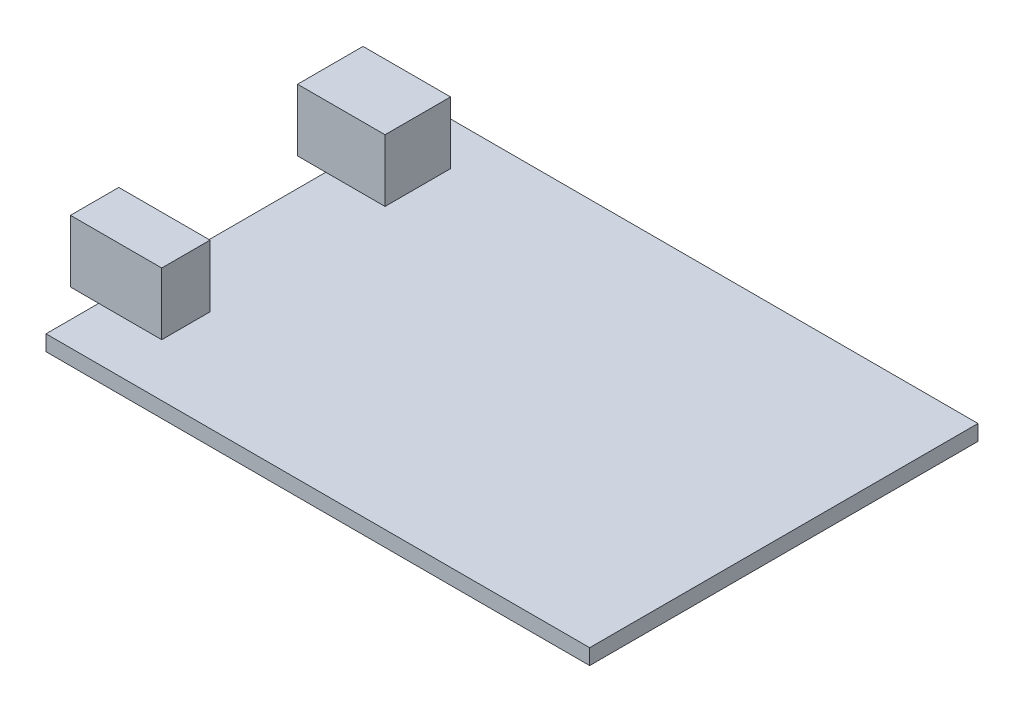
SolidWorks part; units mm, degrees
ref_plane "前视基准面" through (0, 0, 0) normal (0, 0, 1) x (1, 0, 0)
ref_plane "上视基准面" through (0, 0, 0) normal (0, 1, 0) x (1, 0, 0)
ref_plane "右视基准面" through (0, 0, 0) normal (1, 0, 0) x (0, 0, -1)
sketch "草图1" plane through (0, 0, 0) normal (0, 1, 0) x (1, 0, 0)
  line L1 (-22.2992, 9.5983) -> (47.7008, 9.5983)
  line L2 (-22.2992, 9.5983) -> (-22.2992, -40.4017)
  line L3 (-22.2992, -40.4017) -> (47.7008, -40.4017)
  line L4 (47.7008, 9.5983) -> (47.7008, -40.4017)
  line L5 (-22.2992, 9.5983) -> (47.7008, -40.4017) construction
  line L6 (-22.2992, -40.4017) -> (47.7008, 9.5983) construction
  point P4 (12.7008, -15.4017)
  dimension "D1" = 70
  dimension "D2" = 50
extrude "凸台-拉伸1" add sketch "草图1" along normal blind 2
sketch "草图2" plane through (0, 2, 0) normal (0, 1, 0) x (1, 0, 0)
  line L1 (-25.936, 4.055) -> (-14.6698, 4.055)
  line L2 (-25.936, 4.055) -> (-25.936, -4.3774)
  line L3 (-25.936, -4.3774) -> (-14.6698, -4.3774)
  line L4 (-14.6698, 4.055) -> (-14.6698, -4.3774)
  line L5 (-25.936, 4.055) -> (-14.6698, -4.3774) construction
  line L6 (-25.936, -4.3774) -> (-14.6698, 4.055) construction
  line L7 (-25.936, -27.3936) -> (-14.186, -27.3936)
  line L8 (-25.936, -27.3936) -> (-25.936, -33.6142)
  line L9 (-25.936, -33.6142) -> (-14.186, -33.6142)
  line L10 (-14.186, -27.3936) -> (-14.186, -33.6142)
  line L11 (-25.936, -27.3936) -> (-14.186, -33.6142) construction
  line L12 (-25.936, -33.6142) -> (-14.186, -27.3936) construction
  point P4 (-20.3029, -0.1612)
  point P9 (-20.061, -30.5039)
extrude "凸台-拉伸2" add sketch "草图2" along normal blind 8
sketch "草图3" plane through (-25.936, 0, 0) normal (-1, 0, 0) x (0, 0, 1)
  line L1 (-2.5659, 3.5924) -> (3.4026, 3.5924)
  line L2 (-2.5659, 3.5924) -> (-2.5659, 5.5541)
  line L3 (-2.5659, 5.5541) -> (3.4026, 5.5541)
  line L4 (3.4026, 3.5924) -> (3.4026, 5.5541)
  line L5 (-2.5659, 3.5924) -> (3.4026, 5.5541) construction
  line L6 (-2.5659, 5.5541) -> (3.4026, 3.5924) construction
  line L7 (-2.5659, 6.7263) -> (3.4026, 6.7263)
  line L8 (-2.5659, 6.7263) -> (-2.5659, 8.4984)
  line L9 (-2.5659, 8.4984) -> (3.4026, 8.4984)
  line L10 (3.4026, 6.7263) -> (3.4026, 8.4984)
  line L11 (-2.5659, 6.7263) -> (3.4026, 8.4984) construction
  line L12 (-2.5659, 8.4984) -> (3.4026, 6.7263) construction
  circle A0 centre (30.5003, 5.5541) radius 2.0733
  point P4 (0.4183, 4.5732)
  point P9 (0.4183, 7.6124)
extrude "切除-拉伸1" cut sketch "草图3" against normal blind 8
